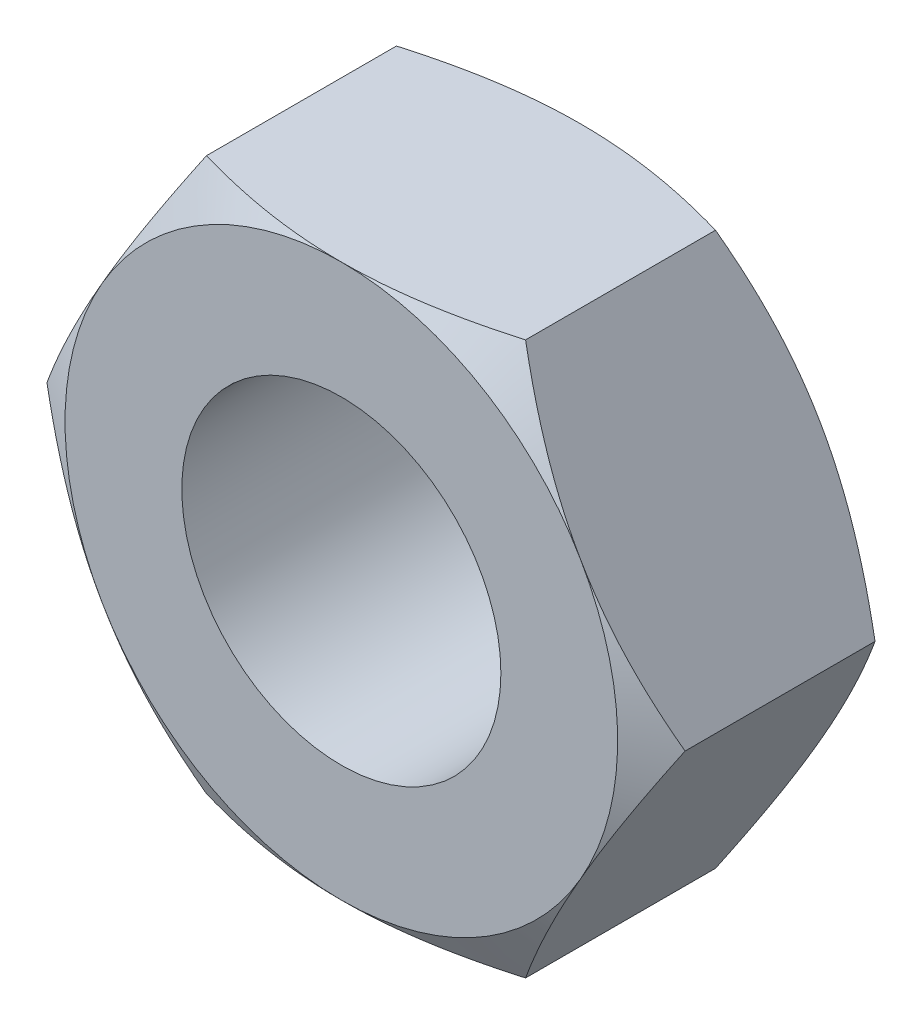
SolidWorks part; units mm, degrees
ref_plane "Front Plane" through (0, 0, 0) normal (0, 0, 1) x (1, 0, 0)
ref_plane "Top Plane" through (0, 0, 0) normal (0, 1, 0) x (1, 0, 0)
ref_plane "Right Plane" through (0, 0, 0) normal (1, 0, 0) x (0, 0, -1)
sketch "Sketch2" plane through (0, 0, 0) normal (0, 0, 1) x (1, 0, 0)
  line L1 (20, 0) -> (10, 17.3205)
  line L2 (10, 17.3205) -> (-10, 17.3205)
  line L3 (-10, 17.3205) -> (-20, 0)
  line L4 (-20, 0) -> (-10, -17.3205)
  line L5 (-10, -17.3205) -> (10, -17.3205)
  line L6 (10, -17.3205) -> (20, 0)
  circle A0 centre (0, 0) radius 17.3205 construction
  circle A1 centre (0, 0) radius 10
  dimension "D2" = 20
  dimension "D1" = 20
extrude "Boss-Extrude1" add sketch "Sketch2" along normal blind 15
sketch "Sketch3" plane through (0, 0, 0) normal (0, 0, -1) x (-1, 0, 0)
  circle A0 centre (0, 0) radius 17.3205
extrude "Cut-Extrude1" cut sketch "Sketch3" against normal blind 15 draft 60 flip side to cut
ref_plane "Plane1" through (0, 0, 7.5) normal (0, 0, -1) x (-1, 0, 0)
mirror "Mirror1" about plane through (0, 0, 7.5) normal (0, 0, -1) of "Cut-Extrude1"
